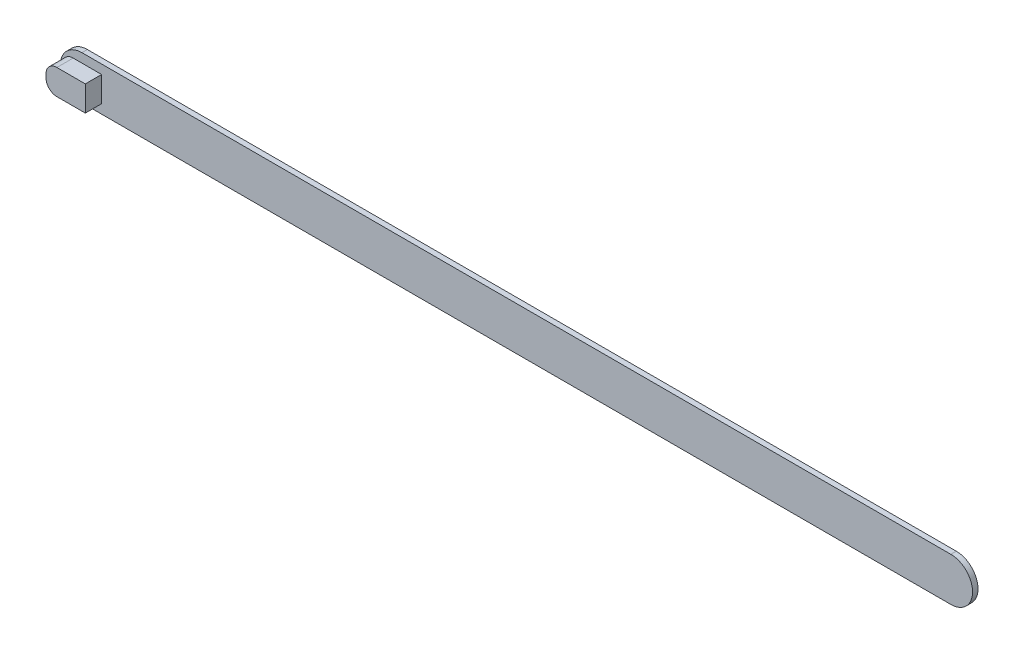
SolidWorks part; units mm, degrees
ref_plane "Front Plane" through (0, 0, 0) normal (0, 0, 1) x (1, 0, 0)
ref_plane "Top Plane" through (0, 0, 0) normal (0, 1, 0) x (1, 0, 0)
ref_plane "Right Plane" through (0, 0, 0) normal (1, 0, 0) x (0, 0, -1)
sketch "Esquisse1" plane through (0, 0, 0) normal (0, 0, 1) x (1, 0, 0)
  line L0 (0, 0) -> (80, 0) construction
  line L1 (0, -2) -> (80, -2)
  line L2 (0, 2) -> (80, 2)
  arc A0 (0, -2) -> (0, 2) centre (0, 0) cw
  arc A1 (80, -2) -> (80, 2) centre (80, 0) ccw
  dimension "D1" = 80
  dimension "D2" = 2
  dimension "D3" = 2
extrude "Boss.-Extru.1" add sketch "Esquisse1" along normal blind 0.5
sketch "Esquisse2" plane through (0, 0, 0.5) normal (0, 0, 1) x (1, 0, 0)
  line L1 (-0.8099, -1.1646) -> (1.8099, -1.1646)
  line L2 (-1.8099, -0.1646) -> (-1.8099, 0.1646)
  line L3 (-0.8099, 1.1646) -> (1.8099, 1.1646)
  line L4 (1.8099, -1.1646) -> (1.8099, 1.1646)
  line L5 (-1.8099, -1.1646) -> (1.8099, 1.1646) construction
  line L6 (-1.8099, 1.1646) -> (1.8099, -1.1646) construction
  arc A0 (-0.8099, -1.1646) -> (-1.8099, -0.1646) centre (-0.8099, -0.1646) cw
  arc A1 (-1.8099, 0.1646) -> (-0.8099, 1.1646) centre (-0.8099, 0.1646) cw
  point P0 (0, 0)
  dimension "D1" = 1
extrude "Boss.-Extru.2" add sketch "Esquisse2" along normal blind 1.5
